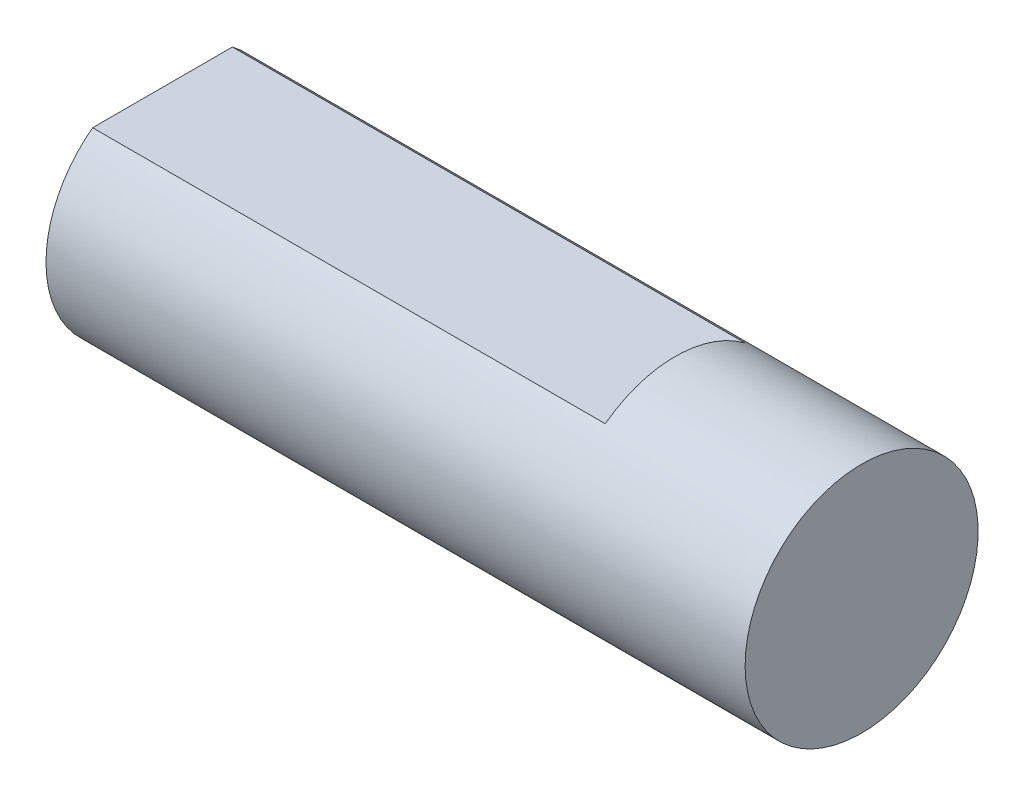
SolidWorks part; units mm, degrees
ref_plane "前视基准面" through (0, 0, 0) normal (0, 0, 1) x (1, 0, 0)
ref_plane "上视基准面" through (0, 0, 0) normal (0, 1, 0) x (1, 0, 0)
ref_plane "右视基准面" through (0, 0, 0) normal (1, 0, 0) x (0, 0, -1)
sketch "Sketch1" plane through (0, 0, 0) normal (0, 0, 1) x (1, 0, 0)
  line L1 (-7.5, 1.25) -> (7.5, 1.25)
  line L2 (-7.5, 1.25) -> (-7.5, -1.25)
  line L3 (-7.5, -1.25) -> (7.5, -1.25)
  line L4 (7.5, 1.25) -> (7.5, -1.25)
  line L5 (-7.5, 1.25) -> (7.5, -1.25) construction
  line L6 (-7.5, -1.25) -> (7.5, 1.25) construction
  point P0 (0, 0)
  dimension "D1" = 15
  dimension "D2" = 2.5
revolve "Revolve1" add sketch "Sketch1" angle 360 about L3
sketch "Sketch2" plane through (-7.5, 0, 0) normal (-1, 0, 0) x (0, 0, 1)
  line L0 (-1.453, 0.75) -> (1.2831, 0.75) construction
  line L1 (-1.5, 0.75) -> (1.5, 0.75)
  arc A0 (1.5, 0.75) -> (-1.5, 0.75) centre (0, -1.25) ccw
  dimension "D1" = 2
extrude "Cut-Extrude1" cut sketch "Sketch2" against normal blind 11
